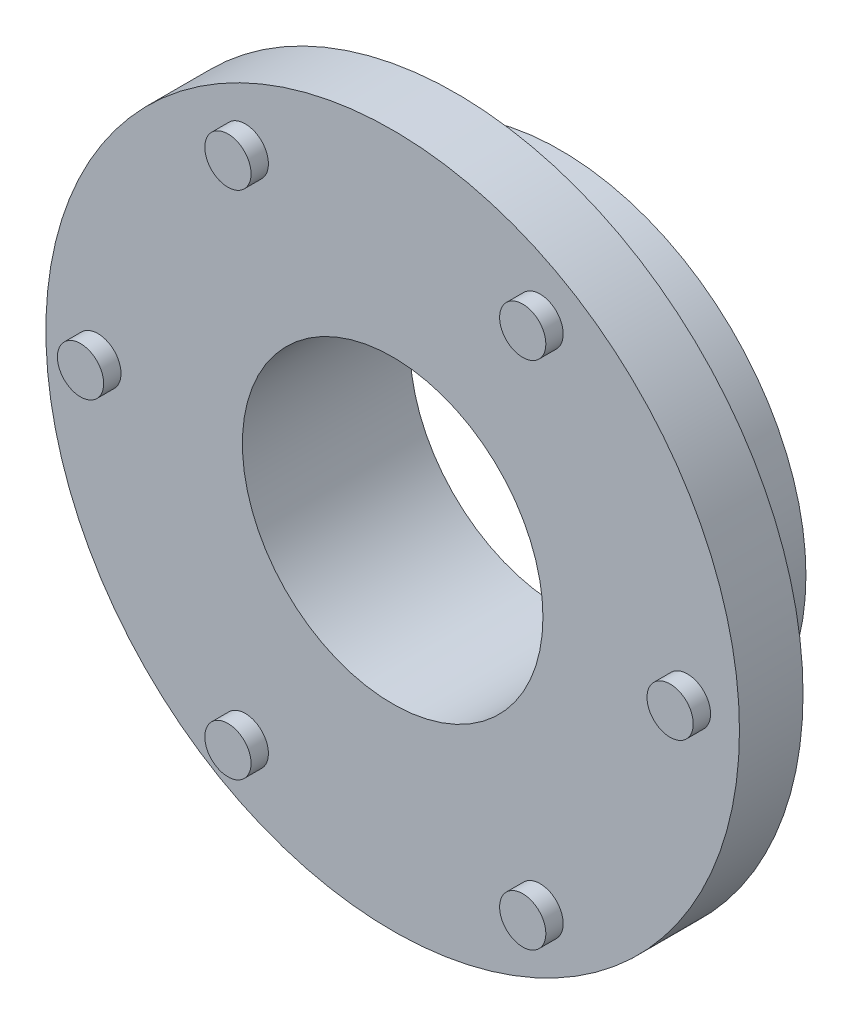
SolidWorks part; units mm, degrees
ref_plane "前视基准面" through (0, 0, 0) normal (0, 0, 1) x (1, 0, 0)
ref_plane "上视基准面" through (0, 0, 0) normal (0, 1, 0) x (1, 0, 0)
ref_plane "右视基准面" through (0, 0, 0) normal (1, 0, 0) x (0, 0, -1)
other "Configuration Table"
sketch "草图1" plane through (0, 0, 0) normal (0, 0, 1) x (1, 0, 0)
  circle A0 centre (0, 0) radius 52
  circle A1 centre (0, 0) radius 85
extrude "凸台-拉伸1" add sketch "草图1" against normal blind 58
sketch "草图2" plane through (0, 0, 0) normal (0, 0, 1) x (1, 0, 0)
  circle A0 centre (0, 0) radius 85
  circle A1 centre (0, 0) radius 120
extrude "凸台-拉伸2" add sketch "草图2" against normal blind 22
sketch "草图3" plane through (0, 0, 0) normal (0, 0, 1) x (1, 0, 0)
  circle A0 centre (102, 0) radius 8
  circle A1 centre (51, 88.3346) radius 8
  circle A2 centre (-51, 88.3346) radius 8
  circle A3 centre (-102, 0) radius 8
  circle A4 centre (-51, -88.3346) radius 8
  circle A5 centre (51, -88.3346) radius 8
extrude "凸台-拉伸3" add sketch "草图3" along normal blind 6
